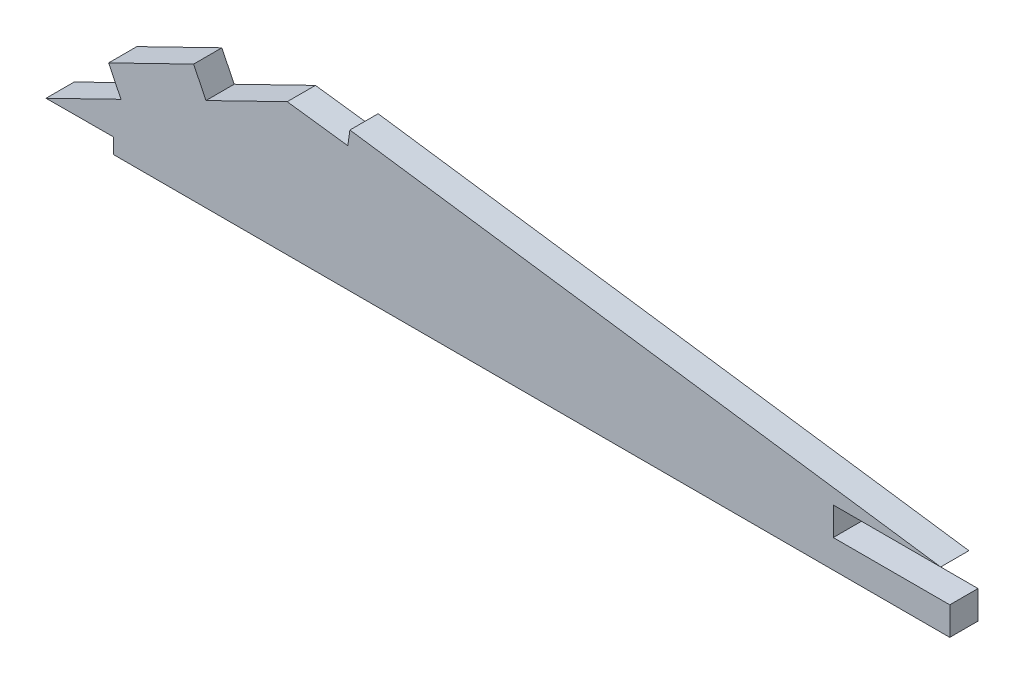
SolidWorks part; units mm, degrees
ref_plane "前视基准面" through (0, 0, 0) normal (0, 0, 1) x (1, 0, 0)
ref_plane "上视基准面" through (0, 0, 0) normal (0, 1, 0) x (1, 0, 0)
ref_plane "右视基准面" through (0, 0, 0) normal (1, 0, 0) x (0, 0, -1)
sketch "Model" plane through (0, 0, 0) normal (0, 0, 1) x (1, 0, 0)
  line L0 (2.0887, 3.9101) -> (7.4032, 6.5022)
  line L1 (6.5265, 8.2998) -> (12.5489, 11.2371)
  line L2 (12.5489, 11.2371) -> (13.4256, 9.4395)
  line L3 (6.5265, 8.2998) -> (7.4032, 6.5022)
  line L4 (13.4256, 9.4395) -> (19.1819, 12.247)
  line L5 (6.8743, 2.8455) -> (66.1354, 2.8455)
  line L6 (6.8743, 2.8455) -> (6.8701, 3.9287)
  line L7 (6.8701, 3.9287) -> (2.0887, 3.9101)
  line L8 (57.8793, 4.8455) -> (66.1354, 4.8455)
  line L9 (57.8793, 6.8455) -> (65.4894, 6.8455)
  line L10 (57.8793, 4.8455) -> (57.8793, 6.8455)
  line L11 (66.1354, 2.8455) -> (66.1354, 4.8455)
  line L12 (23.6243, 12.7293) -> (65.4894, 6.8455)
  line L13 (19.1819, 12.247) -> (23.4761, 11.6916)
  line L14 (23.4761, 11.6916) -> (23.6243, 12.7293)
extrude "凸台-拉伸1" add sketch "Model" along normal blind 2
